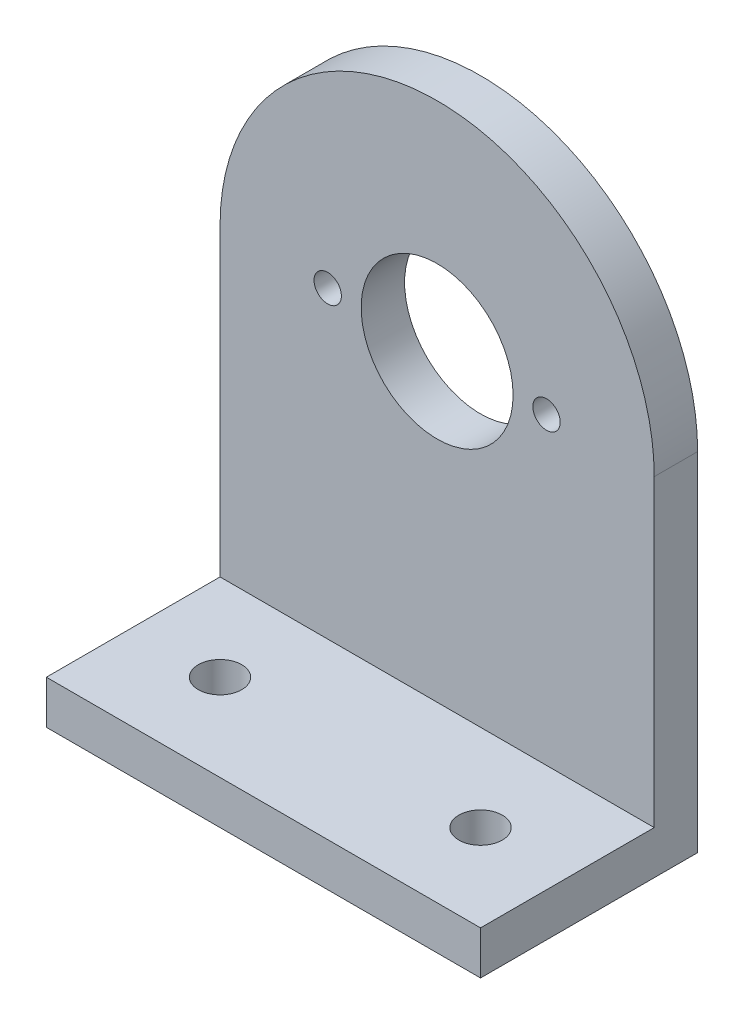
SolidWorks part; units mm, degrees
ref_plane "Front Plane" through (0, 0, 0) normal (0, 0, 1) x (1, 0, 0)
ref_plane "Top Plane" through (0, 0, 0) normal (0, 1, 0) x (1, 0, 0)
ref_plane "Right Plane" through (0, 0, 0) normal (1, 0, 0) x (0, 0, -1)
sketch "Sketch1" plane through (0, 0, 0) normal (0, 0, 1) x (1, 0, 0)
  line L1 (-15.875, 0) -> (15.875, 0)
  line L2 (-15.875, 0) -> (-15.875, -25.4)
  line L3 (-15.875, -25.4) -> (15.875, -25.4)
  line L4 (15.875, 0) -> (15.875, -25.4)
  circle A0 centre (0, 0) radius 15.875
  arc A2 (-15.875, 0) -> (15.875, 0) centre (0, 0) ccw
  dimension "D1" = 31.75
  dimension "D2" = 25.4
extrude "Boss-Extrude1" add sketch "Sketch1" along normal blind 3.175
sketch "Sketch3" plane through (0, 0, 3.175) normal (0, 0, 1) x (1, 0, 0)
  circle A0 centre (0, 0) radius 5.5562
  dimension "D1" = 11.1125
extrude "Cut-Extrude1" cut sketch "Sketch3" against normal through all
sketch "Sketch4" plane through (0, 0, 3.175) normal (0, 0, 1) x (1, 0, 0)
  line L0 (15.875, 0) -> (15.875, -25.4) construction
  line L1 (-15.875, -25.4) -> (15.875, -25.4)
  line L2 (-15.875, -25.4) -> (-15.875, -22.225)
  line L3 (-15.875, -22.225) -> (15.875, -22.225)
  line L4 (15.875, -25.4) -> (15.875, -22.225)
  dimension "D1" = 3.175
extrude "Boss-Extrude2" add sketch "Sketch4" along normal blind 12.7
sketch "Sketch5" plane through (0, -22.225, 0) normal (0, 1, 0) x (1, 0, 0)
  line L0 (-15.875, -9.525) -> (15.875, -9.525) construction
  line L1 (-15.875, -15.875) -> (-15.875, -3.175) construction
  line L2 (15.875, -15.875) -> (15.875, -3.175) construction
  line L3 (0, -3.175) -> (0, -15.875) construction
  line L4 (15.875, -3.175) -> (-15.875, -3.175) construction
  line L5 (15.875, -15.875) -> (-15.875, -15.875) construction
  circle A0 centre (-9.525, -9.525) radius 1.5875
  circle A1 centre (9.525, -9.525) radius 1.5875
  dimension "D1" = 3.175
  dimension "D2" = 9.525
extrude "Cut-Extrude2" cut sketch "Sketch5" against normal through all
hole_wizard "Ø2.0mm Dowel Hole1" positions "Sketch8" profile "Sketch9" hole size "Ø2.0" standard "ANSI Metric"
sketch "Sketch8" plane through (0, 0, 3.175) normal (0, 0, 1) x (1, 0, 0)
  line L0 (-15.875, 0) -> (15.875, 0) construction
  point P0 (-8.001, 0)
  point P2 (8.001, 0)
  dimension "D1" = 16.002
  dimension "D2" = 8.001
sketch "Sketch9" plane through (-8.001, 0, 3.175) normal (1, 0, 0) x (0, -1, 0)
  line L0 (0, 0) -> (0, 13.3009)
  line L1 (0, 13.3009) -> (1, 12.7)
  line L2 (1, 12.7) -> (1, 0)
  line L5 (1, 0) -> (0, 0)
  line L10 (0, 13.3009) -> (-1, 12.7) construction
  line L11 (0, -6.35) -> (0, 107.95) construction
  dimension "Hole Dia." = 2
  dimension "Hole Depth" = 12.7
  dimension "Drill Angle" = 118
